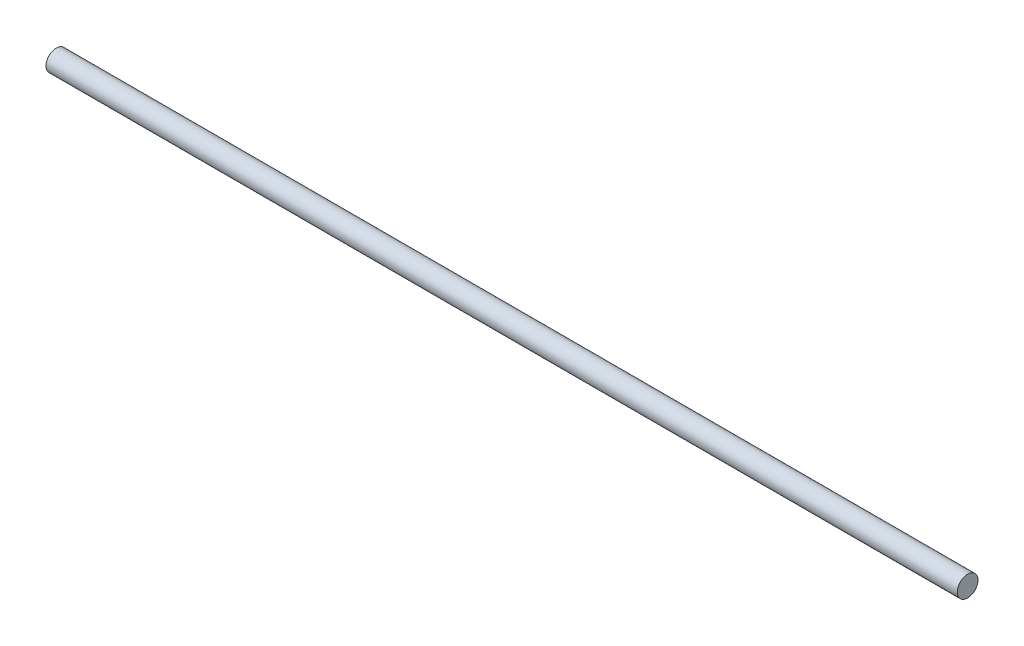
SolidWorks part; units mm, degrees
ref_plane "Front Plane" through (0, 0, 0) normal (0, 0, 1) x (1, 0, 0)
ref_plane "Top Plane" through (0, 0, 0) normal (0, 1, 0) x (1, 0, 0)
ref_plane "Right Plane" through (0, 0, 0) normal (1, 0, 0) x (0, 0, -1)
sketch "Sketch1" plane through (0, 0, 0) normal (1, 0, 0) x (0, 0, -1)
  circle A0 centre (0, 0) radius 1.25
  dimension "D1" = 2.5
extrude "Boss-Extrude1" add sketch "Sketch1" along normal blind 110
